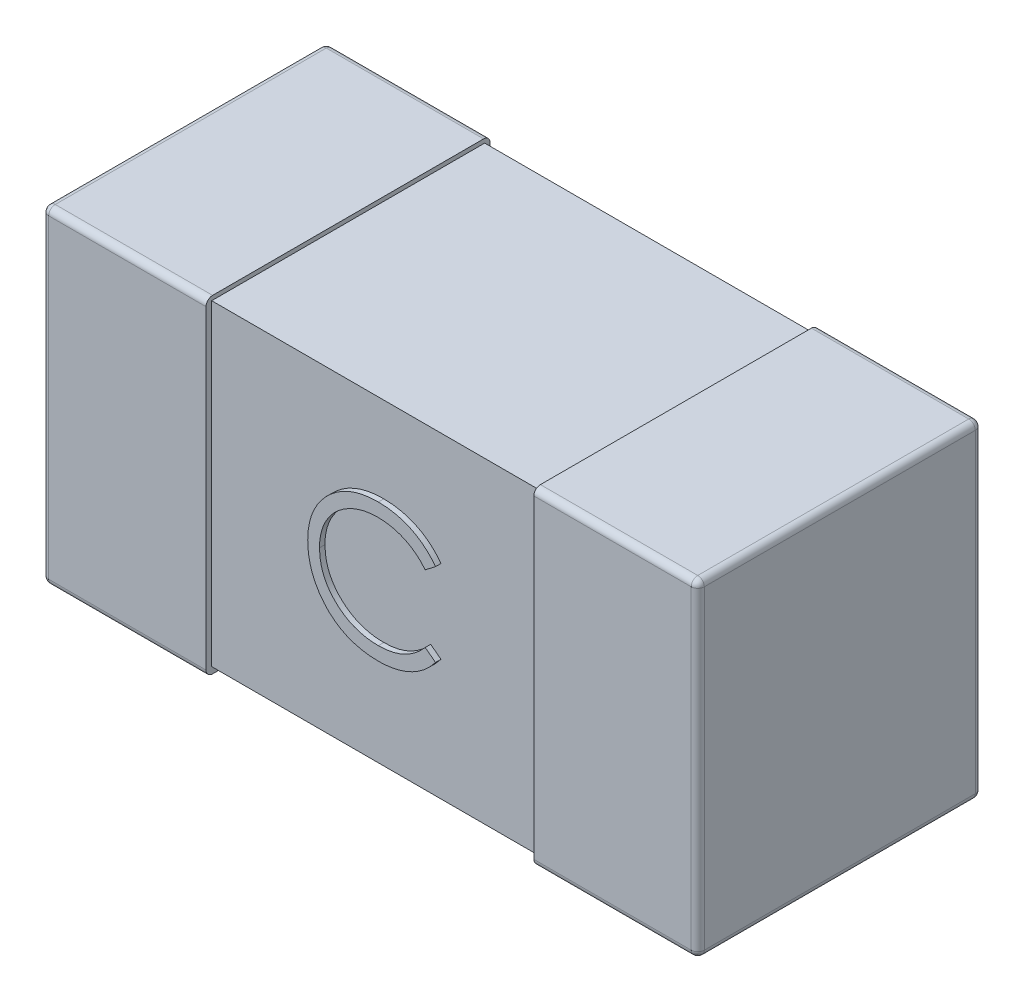
SolidWorks part; units mm, degrees
ref_plane "前视基准面" through (0, 0, 0) normal (0, 0, 1) x (1, 0, 0)
ref_plane "上视基准面" through (0, 0, 0) normal (0, 1, 0) x (1, 0, 0)
ref_plane "右视基准面" through (0, 0, 0) normal (1, 0, 0) x (0, 0, -1)
sketch "草图3" plane through (0, 0, 0) normal (0, 0, 1) x (1, 0, 0)
  line L0 (0, 0.2956) -> (0, -0.3291) construction
  line L1 (-0.3, 0.15) -> (-0.15, 0.15)
  line L2 (-0.3, 0.15) -> (-0.3, -0.15)
  line L3 (-0.3, -0.15) -> (-0.15, -0.15)
  line L4 (-0.15, 0.15) -> (-0.15, -0.15)
  line L5 (-0.3, 0.15) -> (-0.15, -0.15) construction
  line L6 (-0.3, -0.15) -> (-0.15, 0.15) construction
  line L7 (0.3, -0.15) -> (0.15, 0.15) construction
  line L8 (0.3, 0.15) -> (0.15, -0.15) construction
  line L9 (0.15, 0.15) -> (0.15, -0.15)
  line L10 (0.3, -0.15) -> (0.15, -0.15)
  line L11 (0.3, 0.15) -> (0.3, -0.15)
  line L12 (0.3, 0.15) -> (0.15, 0.15)
  point P0 (-0.225, 0)
  point P12 (0.225, 0)
  dimension "D1" = 0.15
  dimension "D2" = 0.3
  dimension "D3" = 0.3
extrude "凸台-拉伸1" add sketch "草图3" along normal blind 0.255 and the other way blind 0.005
sketch "草图5" plane through (0, 0, 0) normal (1, 0, 0) x (0, 0, -1)
  line L1 (0, 0.1462) -> (-0.2498, 0.1462)
  line L2 (0, 0.1462) -> (0, -0.1438)
  line L3 (0, -0.1438) -> (-0.2498, -0.1438)
  line L4 (-0.2498, 0.1462) -> (-0.2498, -0.1438)
  dimension "D1" = 0.2498
  dimension "D2" = 0.29
extrude "凸台-拉伸3" add sketch "草图5" along normal mid plane 0.31
fillet "圆角3" radius 0.006 16 edges at (0.3, 0, -0.005) (0.3, -0.15, 0.125) (0.3, 0, 0.255) (0.3, 0.15, 0.125) (-0.3, 0, -0.005) (-0.3, 0.15, 0.125) (-0.3, 0, 0.255) (-0.3, -0.15, 0.125) (0.225, 0.15, -0.005) (0.225, -0.15, -0.005) (0.225, -0.15, 0.255) (0.225, 0.15, 0.255) (-0.225, -0.15, -0.005) (-0.225, -0.15, 0.255) (-0.225, 0.15, -0.005) (-0.225, 0.15, 0.255)
sketch "草图6" plane through (0, 0, 0.2498) normal (0, 0, 1) x (1, 0, 0)
  text T0 "C" font "Century Gothic" height 0.12
extrude "凸台-拉伸4" add sketch "草图6" along normal blind 0.005
